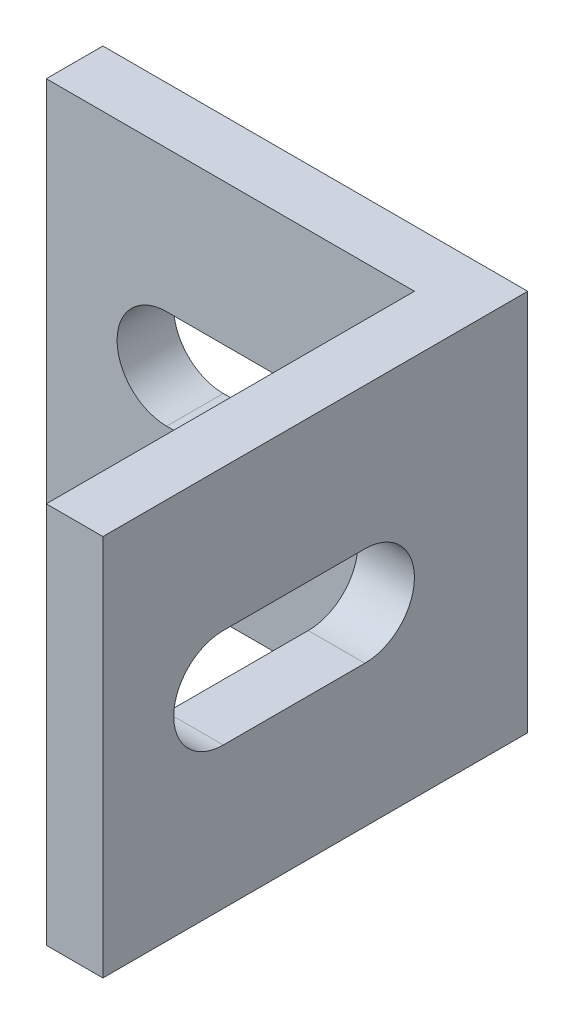
SolidWorks part; units mm, degrees
ref_plane "前视基准面" through (0, 0, 0) normal (0, 0, 1) x (1, 0, 0)
ref_plane "上视基准面" through (0, 0, 0) normal (0, 1, 0) x (1, 0, 0)
ref_plane "右视基准面" through (0, 0, 0) normal (1, 0, 0) x (0, 0, -1)
other "Configuration Table"
sketch "草图1" plane through (0, 0, 0) normal (0, 0, 1) x (1, 0, 0)
  line L0 (8.5, 13.5) -> (18.5, 13.5) construction
  line L1 (0, 0) -> (30, 0)
  line L2 (0, 0) -> (0, 27)
  line L3 (0, 27) -> (30, 27)
  line L4 (30, 0) -> (30, 27)
  line L5 (8.5, 17) -> (18.5, 17)
  line L6 (8.5, 10) -> (18.5, 10)
  arc A0 (8.5, 17) -> (8.5, 10) centre (8.5, 13.5) ccw
  arc A1 (18.5, 10) -> (18.5, 17) centre (18.5, 13.5) ccw
  point P7 (13.5, 13.5)
  point P12 (5, 13.5)
  point P13 (22, 13.5)
  point P15 (30, 13.5)
  dimension "D1" = 27
  dimension "D2" = 30
  dimension "D3" = 17
  dimension "D4" = 7
  dimension "D5" = 5
extrude "凸台-拉伸1" add sketch "草图1" along normal blind 4
sketch "草图2" plane through (0, 0, 4) normal (0, 0, 1) x (1, 0, 0)
  line L0 (0, 0) -> (30, 0) construction
  line L1 (30, 27) -> (26, 27)
  line L2 (30, 27) -> (30, 0)
  line L3 (30, 0) -> (26, 0)
  line L4 (26, 27) -> (26, 0)
  dimension "D1" = 4
extrude "凸台-拉伸2" add sketch "草图2" along normal blind 26
sketch "草图3" plane through (26, 0, 0) normal (-1, 0, 0) x (0, 0, 1)
  line L0 (21.5, 13.5) -> (11.5, 13.5) construction
  line L1 (21.5, 10) -> (11.5, 10)
  line L2 (21.5, 17) -> (11.5, 17)
  line L3 (30, 27) -> (30, 0) construction
  arc A0 (21.5, 10) -> (21.5, 17) centre (21.5, 13.5) ccw
  arc A1 (11.5, 17) -> (11.5, 10) centre (11.5, 13.5) ccw
  point P2 (16.5, 13.5)
  point P7 (8, 13.5)
  point P8 (25, 13.5)
  point P12 (30, 13.5)
  dimension "D1" = 5
  dimension "D2" = 7
  dimension "D3" = 17
extrude "切除-拉伸1" cut sketch "草图3" against normal blind 37
